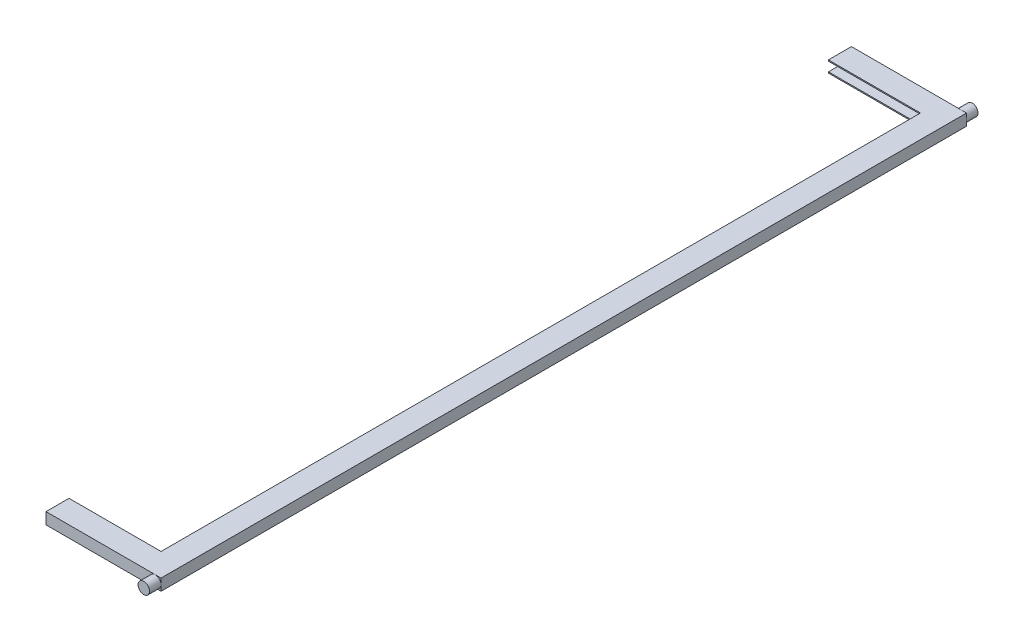
SolidWorks part; units mm, degrees
ref_plane "Alzado" through (0, 0, 0) normal (0, 0, 1) x (1, 0, 0)
ref_plane "Planta" through (0, 0, 0) normal (0, 1, 0) x (1, 0, 0)
ref_plane "Vista lateral" through (0, 0, 0) normal (1, 0, 0) x (0, 0, -1)
sketch "Croquis1" plane through (0, 0, 0) normal (0, 1, 0) x (1, 0, 0)
  line L1 (-50, -350) -> (50, -350)
  line L2 (-50, -350) -> (-50, 350)
  line L3 (-50, 350) -> (50, 350)
  line L4 (50, -350) -> (50, 350)
  line L5 (-50, -350) -> (50, 350) construction
  line L6 (-50, 350) -> (50, -350) construction
  point P0 (0, 0)
  dimension "D1" = 700
  dimension "D2" = 100
extrude "Saliente-Extruir1" add sketch "Croquis1" along normal blind 10
sketch "Croquis2" plane through (0, 0, 350) normal (0, 0, 1) x (1, 0, 0)
  circle A0 centre (45, 5) radius 5
extrude "Saliente-Extruir2" add sketch "Croquis2" along normal blind 10
sketch "Croquis3" plane through (0, 0, -350) normal (0, 0, -1) x (-1, 0, 0)
  line L0 (-50, 10) -> (-50, 0) construction
  circle A0 centre (-45, 5) radius 5
  dimension "D1" = 5
extrude "Saliente-Extruir3" add sketch "Croquis3" along normal blind 10
sketch "Croquis4" plane through (-50, 0, 0) normal (-1, 0, 0) x (0, 0, 1)
  line L0 (0, 0) -> (0, 5)
  line L2 (-349, 9) -> (349, 9)
  line L3 (-349, 9) -> (-349, 1)
  line L4 (-349, 1) -> (349, 1)
  line L5 (349, 9) -> (349, 1)
  line L6 (-349, 9) -> (349, 1) construction
  line L7 (-349, 1) -> (349, 9) construction
  dimension "D1" = 8
  dimension "D2" = 698
extrude "Cortar-Extruir1" cut sketch "Croquis4" against normal blind 90 contours L3 L4 L5 L2
sketch "Croquis5" plane through (0, 10, 0) normal (0, 1, 0) x (1, 0, 0)
  line L0 (-50, 350) -> (-50, -350) construction
  line L1 (-50, 330) -> (30, 330)
  line L2 (-50, 330) -> (-50, -330)
  line L3 (-50, -330) -> (30, -330)
  line L4 (30, 330) -> (30, -330)
  line L5 (45, 350) -> (-50, 350) construction
  line L6 (-50, -350) -> (45, -350) construction
  line L7 (50, -350) -> (50, 350) construction
  dimension "D1" = 20
  dimension "D2" = 20
  dimension "D3" = 20
extrude "Cortar-Extruir2" cut sketch "Croquis5" against normal blind 10
